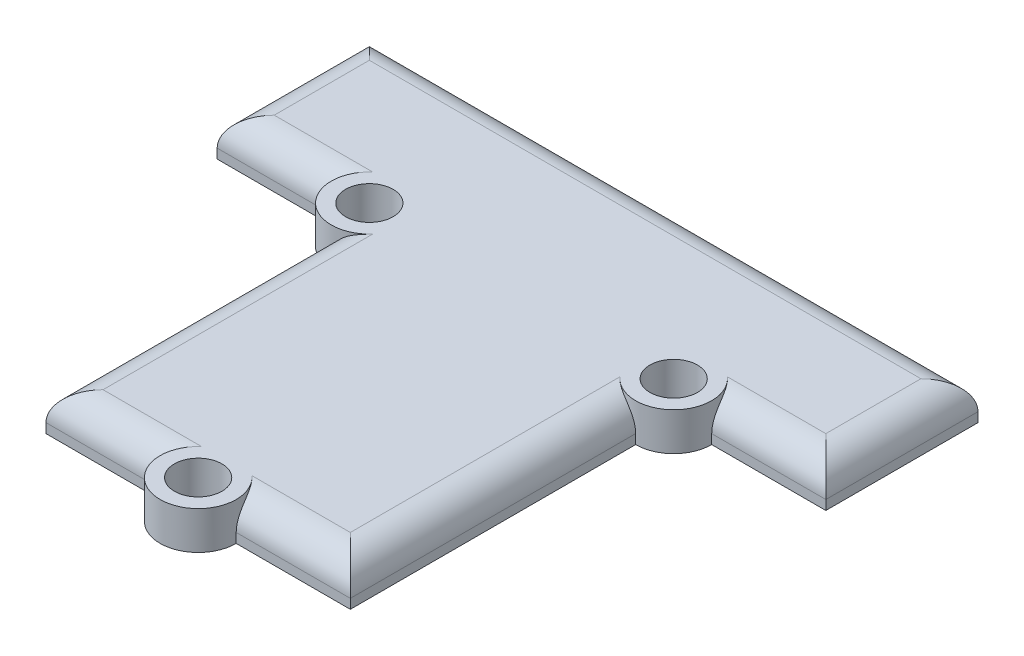
SolidWorks part; units mm, degrees
ref_plane "Plan de face" through (0, 0, 0) normal (0, 0, 1) x (1, 0, 0)
ref_plane "Plan de dessus" through (0, 0, 0) normal (0, 1, 0) x (1, 0, 0)
ref_plane "Plan de droite" through (0, 0, 0) normal (1, 0, 0) x (0, 0, -1)
sketch "Esquisse1" plane through (0, 0, 0) normal (0, 1, 0) x (1, 0, 0)
  line L1 (0, 0) -> (32, 0)
  line L2 (0, 0) -> (0, 8)
  line L3 (0, 8) -> (32, 8)
  line L4 (32, 0) -> (32, 8)
  dimension "D1" = 32
  dimension "D2" = 8
extrude "Boss.-Extru.1" add sketch "Esquisse1" along normal blind 2
sketch "Esquisse2" plane through (0, 2, 0) normal (0, 1, 0) x (1, 0, 0)
  line L0 (0, 0) -> (32, 0) construction
  line L1 (8, 0) -> (24, 0)
  line L2 (8, 0) -> (8, -17)
  line L3 (8, -17) -> (24, -17)
  line L4 (24, 0) -> (24, -17)
  point P6 (16, -17)
  point P7 (16, 0)
  dimension "D1" = 0
  dimension "D2" = 16
  dimension "D3" = 17
extrude "Boss.-Extru.2" add sketch "Esquisse2" against normal blind 2
sketch "Esquisse3" plane through (0, 2, 0) normal (0, 1, 0) x (1, 0, 0)
  line L0 (8, -17) -> (24, -17) construction
  circle A0 centre (8, 0) radius 2
  circle A1 centre (24, 0) radius 2
  circle A2 centre (16, -17) radius 2
  dimension "D1" = 4
  dimension "D2" = 4
  dimension "D3" = 4
extrude "Boss.-Extru.3" add sketch "Esquisse3" against normal blind 2
sketch "Esquisse4" plane through (0, 2, 0) normal (0, 1, 0) x (1, 0, 0)
  circle A0 centre (8, 0) radius 1.25
  circle A1 centre (24, 0) radius 1.25
  circle A2 centre (16, -17) radius 1.25
  dimension "D1" = 2.5
  dimension "D2" = 2.5
  dimension "D3" = 2.5
extrude "Enlèv. mat.-Extru.1" cut sketch "Esquisse4" against normal blind 2
fillet "Congé1" radius 1.5 9 edges at (21, 2, 17) (11, 2, 17) (29, 2, 0) (3, 2, 0) (24, 2, 9.5) (8, 2, 9.5) (32, 2, -4) (0, 2, -4) (16, 2, -8)
